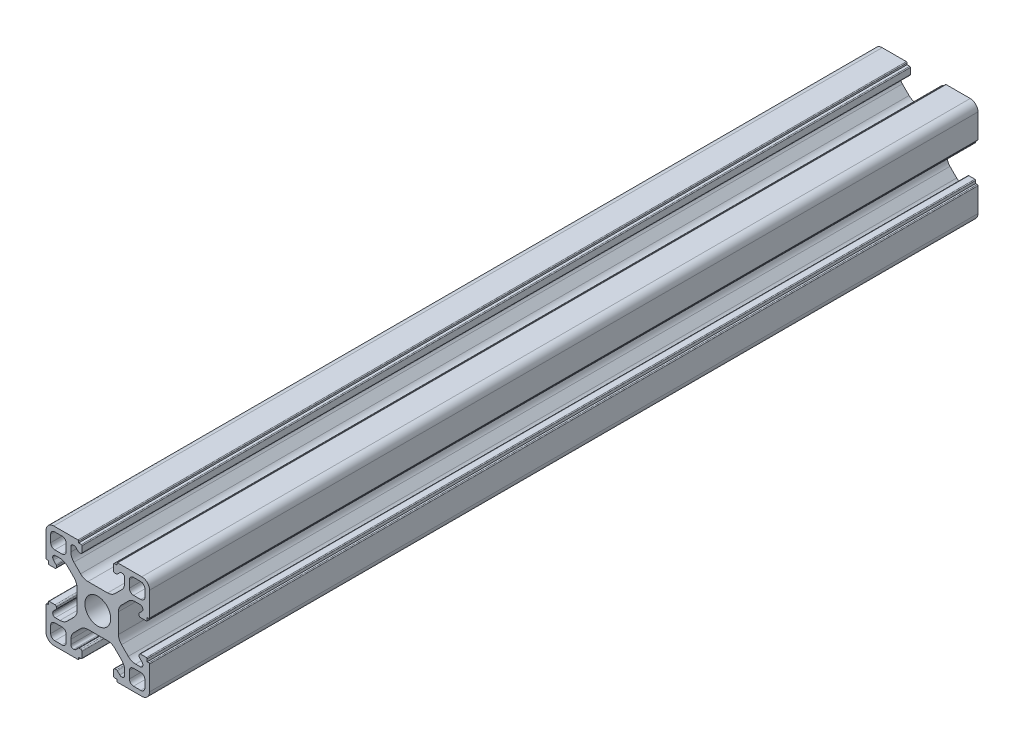
SolidWorks part; units mm, degrees
material "1060 Сплав"
ref_plane "Спереди" through (0, 0, 0) normal (0, 0, 1) x (1, 0, 0)
ref_plane "Сверху" through (0, 0, 0) normal (0, 1, 0) x (1, 0, 0)
ref_plane "Справа" through (0, 0, 0) normal (1, 0, 0) x (0, 0, -1)
sketch "Эскиз1" plane through (0, 0, 0) normal (0, 0, 1) x (1, 0, 0)
  line L0 (-22.0052, 70.3096) -> (-25.0052, 67.3096) construction
  line L1 (-31.1052, 65.2096) -> (-29.2064, 65.2096)
  line L2 (-31.1052, 61.2096) -> (-21.1052, 71.2096) construction
  line L3 (-23.5052, 68.8096) -> (-25.0052, 70.3096) construction
  line L4 (-27.7922, 65.7954) -> (-26.4909, 67.0967)
  line L5 (-24.2052, 67.3096) -> (-22.8052, 67.3096)
  line L6 (-25.0052, 68.1096) -> (-25.0052, 69.5096)
  line L7 (-22.8052, 70.3096) -> (-24.2052, 70.3096)
  line L8 (-25.9052, 69.4096) -> (-25.9052, 68.5109)
  line L9 (-27.3419, 69.2829) -> (-26.8616, 69.7632)
  line L10 (-27.9052, 70.7587) -> (-27.4052, 70.7587)
  line L11 (-27.5187, 69.2096) -> (-27.8052, 69.2096)
  line L12 (-26.508, 69.9096) -> (-26.4052, 69.9096)
  line L13 (-27.4052, 71.0596) -> (-27.4052, 70.7587)
  line L14 (-28.0552, 70.6087) -> (-28.0552, 69.4596)
  line L15 (-22.6052, 71.2096) -> (-27.2552, 71.2096)
  line L16 (-22.0052, 69.5096) -> (-22.0052, 68.1096)
  line L17 (-21.1052, 69.7096) -> (-21.1052, 65.0596)
  line L18 (-21.7061, 64.2596) -> (-22.8552, 64.2596)
  line L19 (-21.2552, 64.9096) -> (-21.5561, 64.9096)
  line L20 (-22.4052, 65.8068) -> (-22.4052, 65.9096)
  line L21 (-23.1052, 64.7961) -> (-23.1052, 64.5096)
  line L22 (-21.5561, 64.4096) -> (-21.5561, 64.9096)
  line L23 (-23.0319, 64.9729) -> (-22.5516, 65.4532)
  line L24 (-22.9052, 66.4096) -> (-23.8039, 66.4096)
  line L25 (-26.5194, 64.5226) -> (-25.2181, 65.8239)
  line L26 (-27.1052, 61.2096) -> (-27.1052, 63.1084)
  line L27 (-27.1052, 61.2096) -> (-27.1052, 59.3109)
  line L28 (-26.5194, 57.8967) -> (-25.2181, 56.5954)
  line L29 (-25.0052, 54.3096) -> (-25.0052, 52.9096)
  line L30 (-24.2052, 55.1096) -> (-22.8052, 55.1096)
  line L31 (-22.0052, 52.9096) -> (-22.0052, 54.3096)
  line L32 (-22.9052, 56.0096) -> (-23.8039, 56.0096)
  line L33 (-23.0319, 57.4464) -> (-22.5516, 56.9661)
  line L34 (-21.5561, 58.0096) -> (-21.5561, 57.5096)
  line L35 (-23.1052, 57.6232) -> (-23.1052, 57.9096)
  line L36 (-22.4052, 56.6125) -> (-22.4052, 56.5096)
  line L37 (-21.2552, 57.5096) -> (-21.5561, 57.5096)
  line L38 (-21.7061, 58.1596) -> (-22.8552, 58.1596)
  line L39 (-21.1052, 52.7096) -> (-21.1052, 57.3596)
  line L40 (-22.8052, 52.1096) -> (-24.2052, 52.1096)
  line L41 (-22.6052, 51.2096) -> (-27.2552, 51.2096)
  line L42 (-28.0552, 51.8106) -> (-28.0552, 52.9596)
  line L43 (-27.4052, 51.3596) -> (-27.4052, 51.6606)
  line L44 (-26.508, 52.5096) -> (-26.4052, 52.5096)
  line L45 (-27.5187, 53.2096) -> (-27.8052, 53.2096)
  line L46 (-27.9052, 51.6606) -> (-27.4052, 51.6606)
  line L47 (-27.3419, 53.1364) -> (-26.8616, 52.6561)
  line L48 (-25.9052, 53.0096) -> (-25.9052, 53.9084)
  line L49 (-27.7922, 56.6239) -> (-26.4909, 55.3226)
  line L50 (-31.1052, 57.2096) -> (-29.2064, 57.2096)
  line L51 (-22.0052, 52.1096) -> (-25.0052, 55.1096) construction
  line L52 (-31.1052, 61.2096) -> (-21.1052, 51.2096) construction
  line L53 (-23.5052, 53.6096) -> (-22.0052, 55.1096) construction
  line L54 (-31.1052, 57.2096) -> (-33.0039, 57.2096)
  line L55 (-34.4181, 56.6239) -> (-35.7194, 55.3226)
  line L56 (-38.0052, 55.1096) -> (-39.4052, 55.1096)
  line L57 (-37.2052, 54.3096) -> (-37.2052, 52.9096)
  line L58 (-39.4052, 52.1096) -> (-38.0052, 52.1096)
  line L59 (-36.3052, 53.0096) -> (-36.3052, 53.9084)
  line L60 (-34.8684, 53.1364) -> (-35.3487, 52.6561)
  line L61 (-34.3052, 51.6606) -> (-34.8052, 51.6606)
  line L62 (-34.6916, 53.2096) -> (-34.4052, 53.2096)
  line L63 (-35.7023, 52.5096) -> (-35.8052, 52.5096)
  line L64 (-34.8052, 51.3596) -> (-34.8052, 51.6606)
  line L65 (-34.1552, 51.8106) -> (-34.1552, 52.9596)
  line L66 (-39.6052, 51.2096) -> (-34.9552, 51.2096)
  line L67 (-40.2052, 52.9096) -> (-40.2052, 54.3096)
  line L68 (-41.1052, 52.7096) -> (-41.1052, 57.3596)
  line L69 (-40.5042, 58.1596) -> (-39.3552, 58.1596)
  line L70 (-40.9552, 57.5096) -> (-40.6542, 57.5096)
  line L71 (-39.8052, 56.6125) -> (-39.8052, 56.5096)
  line L72 (-39.1052, 57.6232) -> (-39.1052, 57.9096)
  line L73 (-40.6542, 58.0096) -> (-40.6542, 57.5096)
  line L74 (-39.1784, 57.4464) -> (-39.6587, 56.9661)
  line L75 (-39.3052, 56.0096) -> (-38.4064, 56.0096)
  line L76 (-35.6909, 57.8967) -> (-36.9922, 56.5954)
  line L77 (-35.1052, 61.2096) -> (-35.1052, 59.3109)
  line L78 (-40.2052, 52.1096) -> (-37.2052, 55.1096) construction
  line L79 (-31.1052, 61.2096) -> (-41.1052, 51.2096) construction
  line L80 (-38.7052, 53.6096) -> (-37.2052, 52.1096) construction
  line L81 (-35.1052, 61.2096) -> (-35.1052, 63.1084)
  line L82 (-35.6909, 64.5226) -> (-36.9922, 65.8239)
  line L83 (-37.2052, 68.1096) -> (-37.2052, 69.5096)
  line L84 (-38.0052, 67.3096) -> (-39.4052, 67.3096)
  line L85 (-40.2052, 69.5096) -> (-40.2052, 68.1096)
  line L86 (-39.3052, 66.4096) -> (-38.4064, 66.4096)
  line L87 (-39.1784, 64.9729) -> (-39.6587, 65.4532)
  line L88 (-40.6542, 64.4096) -> (-40.6542, 64.9096)
  line L89 (-39.1052, 64.7961) -> (-39.1052, 64.5096)
  line L90 (-39.8052, 65.8068) -> (-39.8052, 65.9096)
  line L91 (-40.9552, 64.9096) -> (-40.6542, 64.9096)
  line L92 (-40.5042, 64.2596) -> (-39.3552, 64.2596)
  line L93 (-41.1052, 69.7096) -> (-41.1052, 65.0596)
  line L94 (-39.4052, 70.3096) -> (-38.0052, 70.3096)
  line L95 (-39.6052, 71.2096) -> (-34.9552, 71.2096)
  line L96 (-34.1552, 70.6087) -> (-34.1552, 69.4596)
  line L97 (-34.8052, 71.0596) -> (-34.8052, 70.7587)
  line L98 (-35.7023, 69.9096) -> (-35.8052, 69.9096)
  line L99 (-34.6916, 69.2096) -> (-34.4052, 69.2096)
  line L100 (-34.3052, 70.7587) -> (-34.8052, 70.7587)
  line L101 (-34.8684, 69.2829) -> (-35.3487, 69.7632)
  line L102 (-36.3052, 69.4096) -> (-36.3052, 68.5109)
  line L103 (-34.4181, 65.7954) -> (-35.7194, 67.0967)
  line L104 (-31.1052, 65.2096) -> (-33.0039, 65.2096)
  line L105 (-42.8692, 61.2096) -> (-19.6008, 61.2096) construction
  line L106 (-40.2052, 70.3096) -> (-37.2052, 67.3096) construction
  line L107 (-31.1052, 49.1232) -> (-31.1052, 71.9286) construction
  line L108 (-31.1052, 61.2096) -> (-41.1052, 71.2096) construction
  line L109 (-38.7052, 68.8096) -> (-40.2052, 67.3096) construction
  arc A0 (-22.0052, 69.5096) -> (-22.8052, 70.3096) centre (-22.8052, 69.5096) ccw
  arc A1 (-24.2052, 70.3096) -> (-25.0052, 69.5096) centre (-24.2052, 69.5096) ccw
  arc A2 (-24.2052, 67.3096) -> (-25.0052, 68.1096) centre (-24.2052, 68.1096) cw
  arc A3 (-22.6052, 71.2096) -> (-21.1052, 69.7096) centre (-22.6052, 69.7096) cw
  arc A4 (-27.9052, 70.7587) -> (-28.0552, 70.6087) centre (-27.9052, 70.6087) ccw
  arc A5 (-27.2552, 71.2096) -> (-27.4052, 71.0596) centre (-27.2552, 71.0596) ccw
  arc A6 (-27.5187, 69.2096) -> (-27.3419, 69.2829) centre (-27.5187, 69.4596) ccw
  arc A7 (-27.8052, 69.2096) -> (-28.0552, 69.4596) centre (-27.8052, 69.4596) cw
  arc A8 (-26.8616, 69.7632) -> (-26.508, 69.9096) centre (-26.508, 69.4096) cw
  arc A9 (-26.4052, 69.9096) -> (-25.9052, 69.4096) centre (-26.4052, 69.4096) cw
  arc A10 (-28.6052, 61.2096) -> (-31.1052, 63.7096) centre (-31.1052, 61.2096) ccw
  arc A11 (-29.2064, 65.2096) -> (-27.7922, 65.7954) centre (-29.2064, 67.2096) ccw
  arc A12 (-25.9052, 68.5109) -> (-26.4909, 67.0967) centre (-27.9052, 68.5109) cw
  arc A13 (-22.0052, 68.1096) -> (-22.8052, 67.3096) centre (-22.8052, 68.1096) cw
  arc A14 (-22.4052, 65.9096) -> (-22.9052, 66.4096) centre (-22.9052, 65.9096) ccw
  arc A15 (-22.5516, 65.4532) -> (-22.4052, 65.8068) centre (-22.9052, 65.8068) ccw
  arc A16 (-23.1052, 64.5096) -> (-22.8552, 64.2596) centre (-22.8552, 64.5096) ccw
  arc A17 (-23.1052, 64.7961) -> (-23.0319, 64.9729) centre (-22.8552, 64.7961) cw
  arc A18 (-21.1052, 65.0596) -> (-21.2552, 64.9096) centre (-21.2552, 65.0596) cw
  arc A19 (-21.5561, 64.4096) -> (-21.7061, 64.2596) centre (-21.7061, 64.4096) cw
  arc A20 (-23.8039, 66.4096) -> (-25.2181, 65.8239) centre (-23.8039, 64.4096) ccw
  arc A21 (-27.1052, 63.1084) -> (-26.5194, 64.5226) centre (-25.1052, 63.1084) cw
  arc A22 (-22.8052, 52.1096) -> (-22.0052, 52.9096) centre (-22.8052, 52.9096) ccw
  arc A23 (-22.0052, 54.3096) -> (-22.8052, 55.1096) centre (-22.8052, 54.3096) ccw
  arc A24 (-25.0052, 54.3096) -> (-24.2052, 55.1096) centre (-24.2052, 54.3096) cw
  arc A25 (-21.1052, 52.7096) -> (-22.6052, 51.2096) centre (-22.6052, 52.7096) cw
  arc A26 (-21.5561, 58.0096) -> (-21.7061, 58.1596) centre (-21.7061, 58.0096) ccw
  arc A27 (-21.1052, 57.3596) -> (-21.2552, 57.5096) centre (-21.2552, 57.3596) ccw
  arc A28 (-23.1052, 57.6232) -> (-23.0319, 57.4464) centre (-22.8552, 57.6232) ccw
  arc A29 (-23.1052, 57.9096) -> (-22.8552, 58.1596) centre (-22.8552, 57.9096) cw
  arc A30 (-22.5516, 56.9661) -> (-22.4052, 56.6125) centre (-22.9052, 56.6125) cw
  arc A31 (-22.4052, 56.5096) -> (-22.9052, 56.0096) centre (-22.9052, 56.5096) cw
  arc A32 (-31.1052, 58.7096) -> (-28.6052, 61.2096) centre (-31.1052, 61.2096) ccw
  arc A33 (-27.1052, 59.3109) -> (-26.5194, 57.8967) centre (-25.1052, 59.3109) ccw
  arc A34 (-23.8039, 56.0096) -> (-25.2181, 56.5954) centre (-23.8039, 58.0096) cw
  arc A35 (-24.2052, 52.1096) -> (-25.0052, 52.9096) centre (-24.2052, 52.9096) cw
  arc A36 (-26.4052, 52.5096) -> (-25.9052, 53.0096) centre (-26.4052, 53.0096) ccw
  arc A37 (-26.8616, 52.6561) -> (-26.508, 52.5096) centre (-26.508, 53.0096) ccw
  arc A38 (-27.8052, 53.2096) -> (-28.0552, 52.9596) centre (-27.8052, 52.9596) ccw
  arc A39 (-27.5187, 53.2096) -> (-27.3419, 53.1364) centre (-27.5187, 52.9596) cw
  arc A40 (-27.2552, 51.2096) -> (-27.4052, 51.3596) centre (-27.2552, 51.3596) cw
  arc A41 (-27.9052, 51.6606) -> (-28.0552, 51.8106) centre (-27.9052, 51.8106) cw
  arc A42 (-25.9052, 53.9084) -> (-26.4909, 55.3226) centre (-27.9052, 53.9084) ccw
  arc A43 (-29.2064, 57.2096) -> (-27.7922, 56.6239) centre (-29.2064, 55.2096) cw
  arc A44 (-40.2052, 52.9096) -> (-39.4052, 52.1096) centre (-39.4052, 52.9096) ccw
  arc A45 (-38.0052, 52.1096) -> (-37.2052, 52.9096) centre (-38.0052, 52.9096) ccw
  arc A46 (-38.0052, 55.1096) -> (-37.2052, 54.3096) centre (-38.0052, 54.3096) cw
  arc A47 (-39.6052, 51.2096) -> (-41.1052, 52.7096) centre (-39.6052, 52.7096) cw
  arc A48 (-34.3052, 51.6606) -> (-34.1552, 51.8106) centre (-34.3052, 51.8106) ccw
  arc A49 (-34.9552, 51.2096) -> (-34.8052, 51.3596) centre (-34.9552, 51.3596) ccw
  arc A50 (-34.6916, 53.2096) -> (-34.8684, 53.1364) centre (-34.6916, 52.9596) ccw
  arc A51 (-34.4052, 53.2096) -> (-34.1552, 52.9596) centre (-34.4052, 52.9596) cw
  arc A52 (-35.3487, 52.6561) -> (-35.7023, 52.5096) centre (-35.7023, 53.0096) cw
  arc A53 (-35.8052, 52.5096) -> (-36.3052, 53.0096) centre (-35.8052, 53.0096) cw
  arc A54 (-33.6052, 61.2096) -> (-31.1052, 58.7096) centre (-31.1052, 61.2096) ccw
  arc A55 (-33.0039, 57.2096) -> (-34.4181, 56.6239) centre (-33.0039, 55.2096) ccw
  arc A56 (-36.3052, 53.9084) -> (-35.7194, 55.3226) centre (-34.3052, 53.9084) cw
  arc A57 (-40.2052, 54.3096) -> (-39.4052, 55.1096) centre (-39.4052, 54.3096) cw
  arc A58 (-39.8052, 56.5096) -> (-39.3052, 56.0096) centre (-39.3052, 56.5096) ccw
  arc A59 (-39.6587, 56.9661) -> (-39.8052, 56.6125) centre (-39.3052, 56.6125) ccw
  arc A60 (-39.1052, 57.9096) -> (-39.3552, 58.1596) centre (-39.3552, 57.9096) ccw
  arc A61 (-39.1052, 57.6232) -> (-39.1784, 57.4464) centre (-39.3552, 57.6232) cw
  arc A62 (-41.1052, 57.3596) -> (-40.9552, 57.5096) centre (-40.9552, 57.3596) cw
  arc A63 (-40.6542, 58.0096) -> (-40.5042, 58.1596) centre (-40.5042, 58.0096) cw
  arc A64 (-38.4064, 56.0096) -> (-36.9922, 56.5954) centre (-38.4064, 58.0096) ccw
  arc A65 (-35.1052, 59.3109) -> (-35.6909, 57.8967) centre (-37.1052, 59.3109) cw
  arc A66 (-39.4052, 70.3096) -> (-40.2052, 69.5096) centre (-39.4052, 69.5096) ccw
  arc A67 (-40.2052, 68.1096) -> (-39.4052, 67.3096) centre (-39.4052, 68.1096) ccw
  arc A68 (-37.2052, 68.1096) -> (-38.0052, 67.3096) centre (-38.0052, 68.1096) cw
  arc A69 (-41.1052, 69.7096) -> (-39.6052, 71.2096) centre (-39.6052, 69.7096) cw
  arc A70 (-40.6542, 64.4096) -> (-40.5042, 64.2596) centre (-40.5042, 64.4096) ccw
  arc A71 (-41.1052, 65.0596) -> (-40.9552, 64.9096) centre (-40.9552, 65.0596) ccw
  arc A72 (-39.1052, 64.7961) -> (-39.1784, 64.9729) centre (-39.3552, 64.7961) ccw
  arc A73 (-39.1052, 64.5096) -> (-39.3552, 64.2596) centre (-39.3552, 64.5096) cw
  arc A74 (-39.6587, 65.4532) -> (-39.8052, 65.8068) centre (-39.3052, 65.8068) cw
  arc A75 (-39.8052, 65.9096) -> (-39.3052, 66.4096) centre (-39.3052, 65.9096) cw
  arc A76 (-31.1052, 63.7096) -> (-33.6052, 61.2096) centre (-31.1052, 61.2096) ccw
  arc A77 (-35.1052, 63.1084) -> (-35.6909, 64.5226) centre (-37.1052, 63.1084) ccw
  arc A78 (-38.4064, 66.4096) -> (-36.9922, 65.8239) centre (-38.4064, 64.4096) cw
  arc A79 (-38.0052, 70.3096) -> (-37.2052, 69.5096) centre (-38.0052, 69.5096) cw
  arc A80 (-35.8052, 69.9096) -> (-36.3052, 69.4096) centre (-35.8052, 69.4096) ccw
  arc A81 (-35.3487, 69.7632) -> (-35.7023, 69.9096) centre (-35.7023, 69.4096) ccw
  arc A82 (-34.4052, 69.2096) -> (-34.1552, 69.4596) centre (-34.4052, 69.4596) ccw
  arc A83 (-34.6916, 69.2096) -> (-34.8684, 69.2829) centre (-34.6916, 69.4596) cw
  arc A84 (-34.9552, 71.2096) -> (-34.8052, 71.0596) centre (-34.9552, 71.0596) cw
  arc A85 (-34.3052, 70.7587) -> (-34.1552, 70.6087) centre (-34.3052, 70.6087) cw
  arc A86 (-36.3052, 68.5109) -> (-35.7194, 67.0967) centre (-34.3052, 68.5109) ccw
  arc A87 (-33.0039, 65.2096) -> (-34.4181, 65.7954) centre (-33.0039, 67.2096) cw
  point P0 (-31.1052, 61.2096)
  point P9 (-31.1052, 61.2096)
  point P40 (-22.4052, 64.9096)
  point P93 (-27.4052, 52.5096)
  point P144 (-27.4052, 69.9096)
  point P152 (-22.4052, 57.5096)
  point P153 (-31.1052, 57.2854)
  point P154 (-31.1052, 61.2096)
  point P189 (-39.8052, 57.5096)
  point P228 (-34.8052, 52.5096)
  point P229 (-35.0294, 61.2096)
  point P230 (-31.1052, 61.2096)
  point P268 (-34.8052, 69.9096)
  point P273 (-27.1809, 61.2096)
  point P306 (-39.8052, 64.9096)
  point P307 (-31.1052, 65.1339)
  point P309 (-31.1052, 61.2096)
  dimension "D3" = 5
  dimension "D6" = 2
  dimension "D1" = 2
  dimension "D2" = 6
  dimension "D4" = 4
  dimension "D5" = 0.9
extrude "Бобышка-Вытянуть1" add sketch "Эскиз1" along normal blind 160
